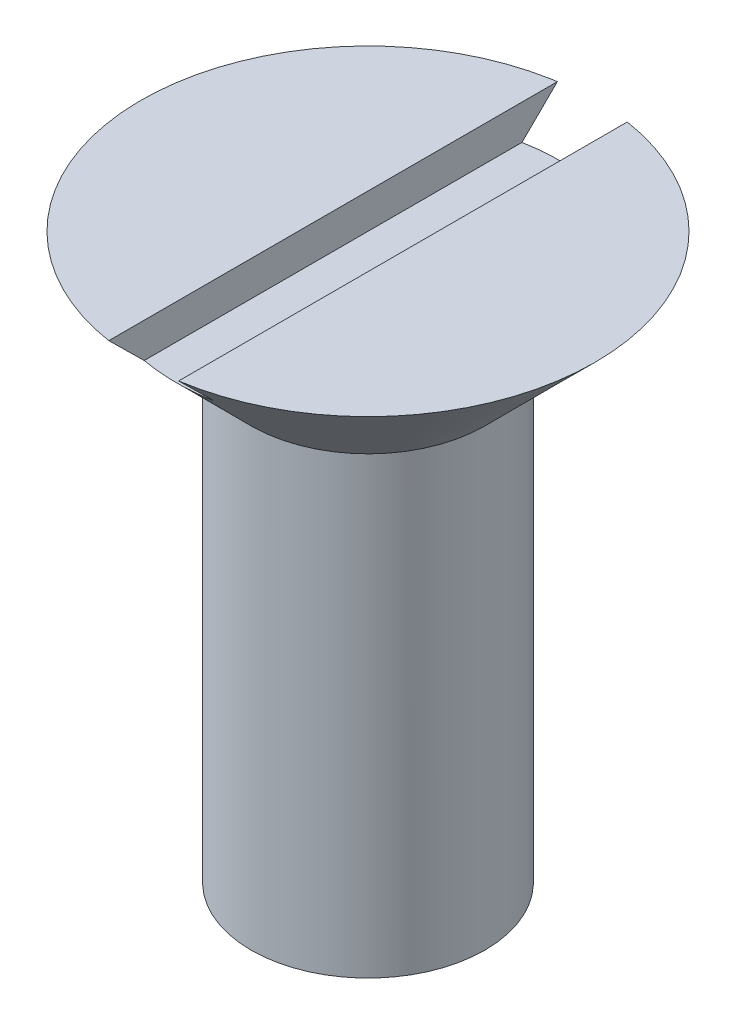
SolidWorks part; units mm, degrees
material "AISI 4340 Steel, normalized"
ref_plane "Front Plane" through (0, 0, 0) normal (0, 0, 1) x (1, 0, 0)
ref_plane "Top Plane" through (0, 0, 0) normal (0, 1, 0) x (1, 0, 0)
ref_plane "Right Plane" through (0, 0, 0) normal (1, 0, 0) x (0, 0, -1)
sketch "Sketch1" plane through (0, 0, 0) normal (0, 0, 1) x (1, 0, 0)
  line L0 (0, -6.8488) -> (0, 8.3024) construction
  line L1 (-3.3488, -6.8488) -> (0, -6.8488)
  line L2 (0, 2.8024) -> (-6.5, 9.3024) construction
  line L3 (-3.3488, 6.1512) -> (0, 6.1512)
  line L4 (-3.3488, 6.1512) -> (-3.3488, -6.8488)
  line L5 (0, 0) -> (-3.3488, -6.8488) construction
  line L6 (0, 0) -> (-3.3488, 6.1512) construction
  line L7 (0, 8.3024) -> (-1, 8.3024)
  line L8 (-1, 8.3024) -> (-1, 9.3024)
  line L9 (-1, 9.3024) -> (-6.5, 9.3024)
  line L11 (-6.5, 9.3024) -> (-3.3488, 6.1512)
  line L12 (0, 8.3024) -> (0, -6.8488)
  point P0 (0, 0)
  dimension "D1" = 13
  dimension "D2" = 1
  dimension "D3" = 1
  dimension "D4" = 5.5
  dimension "D5" = 3.3488
  dimension "D6" = 6.8488
  dimension "D7" = 55.056
revolve "Revolve3" add sketch "Sketch1" angle 360 about L0
sketch "Sketch3" plane through (0, 0, 0) normal (0, 0, 1) x (1, 0, 0)
  line L0 (-1, 9.3024) -> (1, 9.3024)
  line L1 (1, 9.3024) -> (1, 8.3024)
  line L2 (1, 8.3024) -> (-1, 8.3024)
  line L3 (-1, 8.3024) -> (-1, 9.3024)
  dimension "D1" = 1
extrude "Cut-Extrude1" cut sketch "Sketch3" against normal through all both and the other way through all
sketch "Sketch4" plane through (0, 0, 0) normal (1, 0, 0) x (0, 0, -1)
  line L0 (-3.3488, -6.8488) -> (0, -8.7822)
  line L2 (-3.3488, -6.8488) -> (3.3488, -6.8488) construction
  line L3 (0, -7.6367) -> (0, 49992.3633) construction
  line L4 (0, -6.8488) -> (0, -8.7822)
  line L5 (-3.3488, -6.8488) -> (0, -6.8488)
  point P5 (0, -8.7822)
  point P11 (0, -8.7822)
  point P13 (0, -6.8488)
  dimension "D1" = 1.9334
revolve "Revolve4" add sketch "Sketch4" angle 360 about L3
